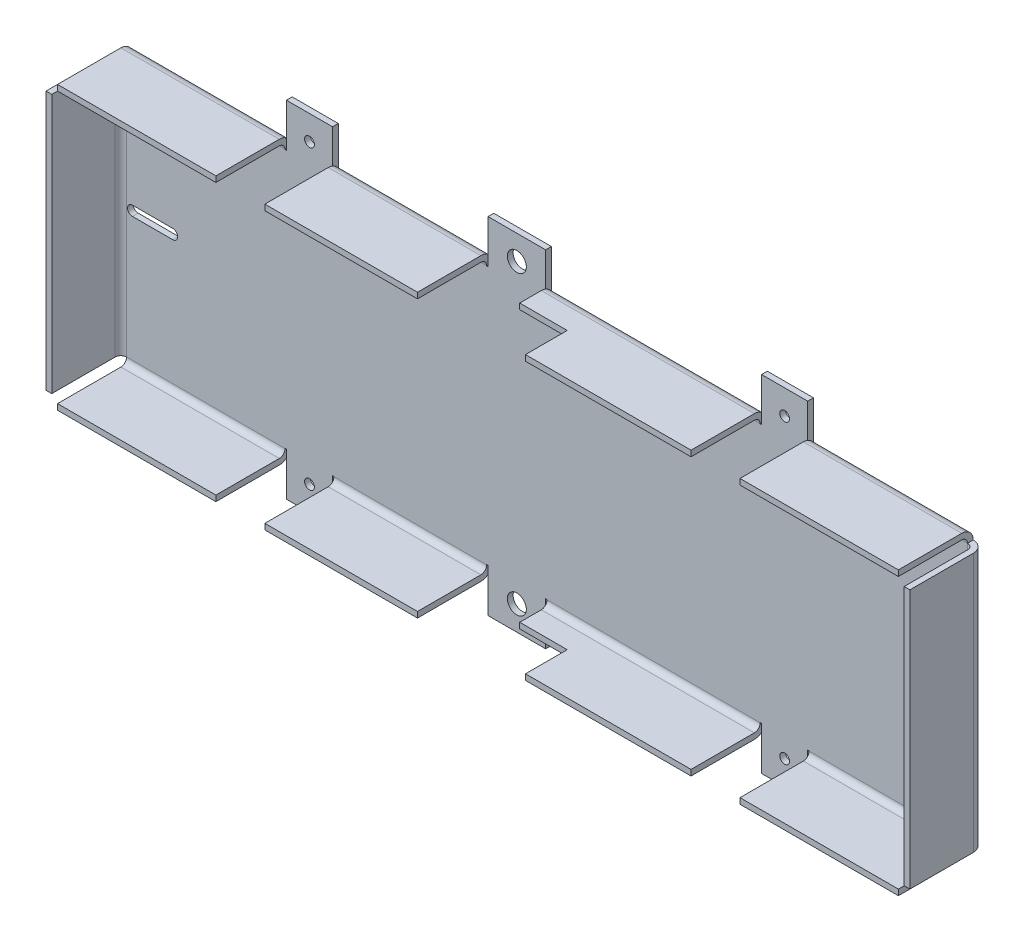
SolidWorks part; units mm, degrees
other "Ballast Tray"
ref_plane "Front Plane" through (0, 0, 0) normal (0, 0, 1) x (1, 0, 0)
ref_plane "Top Plane" through (0, 0, 0) normal (0, 1, 0) x (1, 0, 0)
ref_plane "Right Plane" through (0, 0, 0) normal (1, 0, 0) x (0, 0, -1)
sketch3d "Tray Section Sketch datum points"
  point P0 (-153.5, 0, 0)
  point P1 (-153.5, 10, 0)
  point P2 (-153.5, 0, 10)
ref_plane "Tray Section Sketch plane" through (-153.5, 0, 0) normal (1, 0, 0) x (0, 0, -1)
sketch "Tray Section Sketch" plane through (-153.5, 0, 0) normal (1, 0, 0) x (0, 0, -1)
  line L0 (-144, -49) -> (-122, -49)
  line L1 (-118, -45) -> (-118, 45)
  line L2 (-122, 49) -> (-144, 49)
  line L3 (-144, 49) -> (-144, 47)
  line L4 (-144, 47) -> (-122, 47)
  line L5 (-120, 45) -> (-120, -45)
  line L6 (-122, -47) -> (-144, -47)
  line L7 (-144, -47) -> (-144, -49)
  arc A0 (-122, -49) -> (-118, -45) centre (-122, -45) ccw
  arc A1 (-118, 45) -> (-122, 49) centre (-122, 45) ccw
  arc A2 (-120, 45) -> (-122, 47) centre (-122, 45) ccw
  arc A3 (-122, -47) -> (-120, -45) centre (-122, -45) ccw
extrude "Tray Section" add sketch "Tray Section Sketch" along normal blind 292 separate body
sketch3d "Rear Wall Sketch datum points"
  point P0 (0, -45, 0)
  point P1 (10, -45, 0)
  point P2 (0, -45, 10)
ref_plane "Rear Wall Sketch plane" through (0, -45, 0) normal (0, -1, 0) x (-1, 0, 0)
sketch "Rear Wall Sketch" plane through (0, -45, 0) normal (0, -1, 0) x (-1, 0, 0)
  line L0 (157.5, -122) -> (157.5, -144)
  line L1 (157.5, -144) -> (155.5, -144)
  line L2 (155.5, -144) -> (155.5, -122)
  line L3 (153.5, -120) -> (153.5, -118)
  arc A0 (157.5, -122) -> (153.5, -118) centre (153.5, -122) ccw
  arc A1 (155.5, -122) -> (153.5, -120) centre (153.5, -122) ccw
extrude "Rear Wall" add sketch "Rear Wall Sketch" against normal blind 90
sketch3d "Front Wall Sketch datum points"
  point P0 (0, -45, 0)
  point P1 (10, -45, 0)
  point P2 (0, -45, 10)
ref_plane "Front Wall Sketch plane" through (0, -45, 0) normal (0, -1, 0) x (-1, 0, 0)
sketch "Front Wall Sketch" plane through (0, -45, 0) normal (0, -1, 0) x (-1, 0, 0)
  line L0 (-142.5, -122) -> (-142.5, -144)
  line L1 (-142.5, -144) -> (-140.5, -144)
  line L2 (-140.5, -144) -> (-140.5, -122)
  line L3 (-138.5, -120) -> (-138.5, -118)
  arc A0 (-138.5, -118) -> (-142.5, -122) centre (-138.5, -122) ccw
  arc A1 (-138.5, -120) -> (-140.5, -122) centre (-138.5, -122) ccw
extrude "Front Wall" add sketch "Front Wall Sketch" against normal blind 90
sketch3d "Ear Relief Sketch datum points"
  point P0 (0, 0, 117.8)
  point P1 (10, 0, 117.8)
  point P2 (0, 10, 117.8)
ref_plane "Ear Relief Sketch plane" through (0, 0, 117.8) normal (0, 0, 1) x (1, 0, 0)
sketch "Ear Relief Sketch" plane through (0, 0, 117.8) normal (0, 0, 1) x (1, 0, 0)
  line L0 (-98.5, -49.2) -> (-81.5, -49.2)
  line L1 (-81.5, -49.2) -> (-81.5, -44.9)
  line L2 (-81.5, -44.9) -> (-98.5, -44.9)
  line L3 (-98.5, -44.9) -> (-98.5, -49.2)
  line L4 (-98.5, 44.9) -> (-81.5, 44.9)
  line L5 (-81.5, 44.9) -> (-81.5, 49.2)
  line L6 (-81.5, 49.2) -> (-98.5, 49.2)
  line L7 (-98.5, 49.2) -> (-98.5, 44.9)
  line L8 (66.5, -49.2) -> (83.5, -49.2)
  line L9 (83.5, -49.2) -> (83.5, -44.9)
  line L10 (83.5, -44.9) -> (66.5, -44.9)
  line L11 (66.5, -44.9) -> (66.5, -49.2)
  line L12 (66.5, 44.9) -> (83.5, 44.9)
  line L13 (83.5, 44.9) -> (83.5, 49.2)
  line L14 (83.5, 49.2) -> (66.5, 49.2)
  line L15 (66.5, 49.2) -> (66.5, 44.9)
  line L16 (-28.5, -49.2) -> (-7.5, -49.2)
  line L17 (-7.5, -49.2) -> (-7.5, -44.9)
  line L18 (-7.5, -44.9) -> (-28.5, -44.9)
  line L19 (-28.5, -44.9) -> (-28.5, -49.2)
  line L20 (-28.5, 44.9) -> (-7.5, 44.9)
  line L21 (-7.5, 44.9) -> (-7.5, 49.2)
  line L22 (-7.5, 49.2) -> (-28.5, 49.2)
  line L23 (-28.5, 49.2) -> (-28.5, 44.9)
extrude "Ear Reliefs" cut sketch "Ear Relief Sketch" along normal blind 26.4
sketch3d "Mounting Ear Sketch datum points"
  point P0 (0, 0, 118)
  point P1 (10, 0, 118)
  point P2 (0, 10, 118)
ref_plane "Mounting Ear Sketch plane" through (0, 0, 118) normal (0, 0, 1) x (1, 0, 0)
sketch "Mounting Ear Sketch" plane through (0, 0, 118) normal (0, 0, 1) x (1, 0, 0)
  line L0 (-98, -60) -> (-82, -60)
  line L1 (-82, -60) -> (-82, -44.8)
  line L2 (-82, -44.8) -> (-98, -44.8)
  line L3 (-98, -44.8) -> (-98, -60)
  line L4 (-98, 44.8) -> (-82, 44.8)
  line L5 (-82, 44.8) -> (-82, 60)
  line L6 (-82, 60) -> (-98, 60)
  line L7 (-98, 60) -> (-98, 44.8)
  line L8 (67, -60) -> (83, -60)
  line L9 (83, -60) -> (83, -44.8)
  line L10 (83, -44.8) -> (67, -44.8)
  line L11 (67, -44.8) -> (67, -60)
  line L12 (67, 44.8) -> (83, 44.8)
  line L13 (83, 44.8) -> (83, 60)
  line L14 (83, 60) -> (67, 60)
  line L15 (67, 60) -> (67, 44.8)
  line L16 (-28, -60) -> (-8, -60)
  line L17 (-8, -60) -> (-8, -44.8)
  line L18 (-8, -44.8) -> (-28, -44.8)
  line L19 (-28, -44.8) -> (-28, -60)
  line L20 (-28, 44.8) -> (-8, 44.8)
  line L21 (-8, 44.8) -> (-8, 60)
  line L22 (-8, 60) -> (-28, 60)
  line L23 (-28, 60) -> (-28, 44.8)
extrude "Mounting Ears" add sketch "Mounting Ear Sketch" along normal blind 2
sketch3d "Tray Hole Sketch datum points"
  point P0 (0, 0, 117.8)
  point P1 (10, 0, 117.8)
  point P2 (0, 10, 117.8)
ref_plane "Tray Hole Sketch plane" through (0, 0, 117.8) normal (0, 0, 1) x (1, 0, 0)
sketch "Tray Hole Sketch" plane through (0, 0, 117.8) normal (0, 0, 1) x (1, 0, 0)
  line L0 (-151.5, -1.7) -> (-137.5, -1.7)
  line L1 (-137.5, 1.7) -> (-151.5, 1.7)
  line L2 (122.5, -1.7) -> (136.5, -1.7)
  line L3 (136.5, 1.7) -> (122.5, 1.7)
  circle A0 centre (-90, -51.5) radius 1.7
  circle A1 centre (-90, 51.5) radius 1.7
  circle A2 centre (75, -51.5) radius 1.7
  circle A3 centre (75, 51.5) radius 1.7
  circle A4 centre (-18, -51.5) radius 3.3
  circle A5 centre (-18, 51.5) radius 3.3
  arc A6 (-137.5, -1.7) -> (-137.5, 1.7) centre (-137.5, 0) ccw
  arc A7 (-151.5, 1.7) -> (-151.5, -1.7) centre (-151.5, 0) ccw
  arc A8 (136.5, -1.7) -> (136.5, 1.7) centre (136.5, 0) ccw
  arc A9 (122.5, 1.7) -> (122.5, -1.7) centre (122.5, 0) ccw
extrude "Tray Holes and Slots" cut sketch "Tray Hole Sketch" along normal blind 2.4
sketch3d "Clamp Clearance Sketch datum points"
  point P0 (0, -65, 0)
  point P1 (10, -65, 0)
  point P2 (0, -65, 10)
ref_plane "Clamp Clearance Sketch plane" through (0, -65, 0) normal (0, -1, 0) x (-1, 0, 0)
sketch "Clamp Clearance Sketch" plane through (0, -65, 0) normal (0, -1, 0) x (-1, 0, 0)
  line L0 (24, -129.5) -> (-9, -129.5)
  line L1 (-9, -129.5) -> (-9, -144.2)
  line L2 (-9, -144.2) -> (24, -144.2)
  line L3 (24, -144.2) -> (24, -129.5)
extrude "Clamp Clearance" cut sketch "Clamp Clearance Sketch" against normal blind 130
